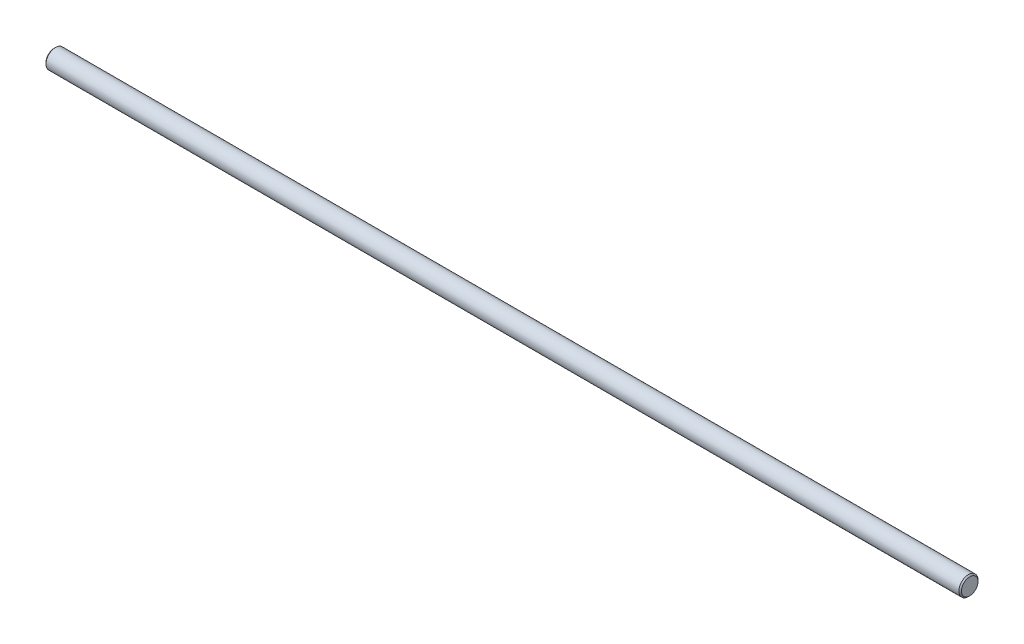
SolidWorks part; units mm, degrees
material "AISI 4130 Steel, normalized at 870C"
ref_plane "Front" through (0, 0, 0) normal (0, 0, 1) x (1, 0, 0)
ref_plane "Top" through (0, 0, 0) normal (0, 1, 0) x (1, 0, 0)
ref_plane "Right" through (0, 0, 0) normal (1, 0, 0) x (0, 0, -1)
sketch "Sketch1" plane through (0, 0, 0) normal (0, 0, 1) x (1, 0, 0)
  line L0 (-228.6, 0) -> (228.6, 0) construction
  line L1 (228.6, 3.175) -> (228.6, -3.175) construction
  line L2 (-228.6, 3.175) -> (-228.6, -3.175) construction
  dimension "Length" = 457.2
  dimension "Diameter" = 6.35
sketch "Sketch2" plane through (0, 0, 0) normal (1, 0, 0) x (0, 0, -1)
  circle A0 centre (0, 0) radius 4.7625
  dimension "D1" = 9.525
extrude "Extrude1" add sketch "Sketch2" against normal up to vertex (228.6 mm away) and the other way up to vertex (228.6 mm away) up to point (-228.6, 3.175, 0) other way up to point (228.6, 3.175, 0)
chamfer "Chamfer1" distance 0.635 angle 45 2 edges at (228.6, 0, -4.7625) (-228.6, 0, -4.7625)
equation "\"D1@Chamfer1\" = \"Diameter@Sketch1\"*.1"
